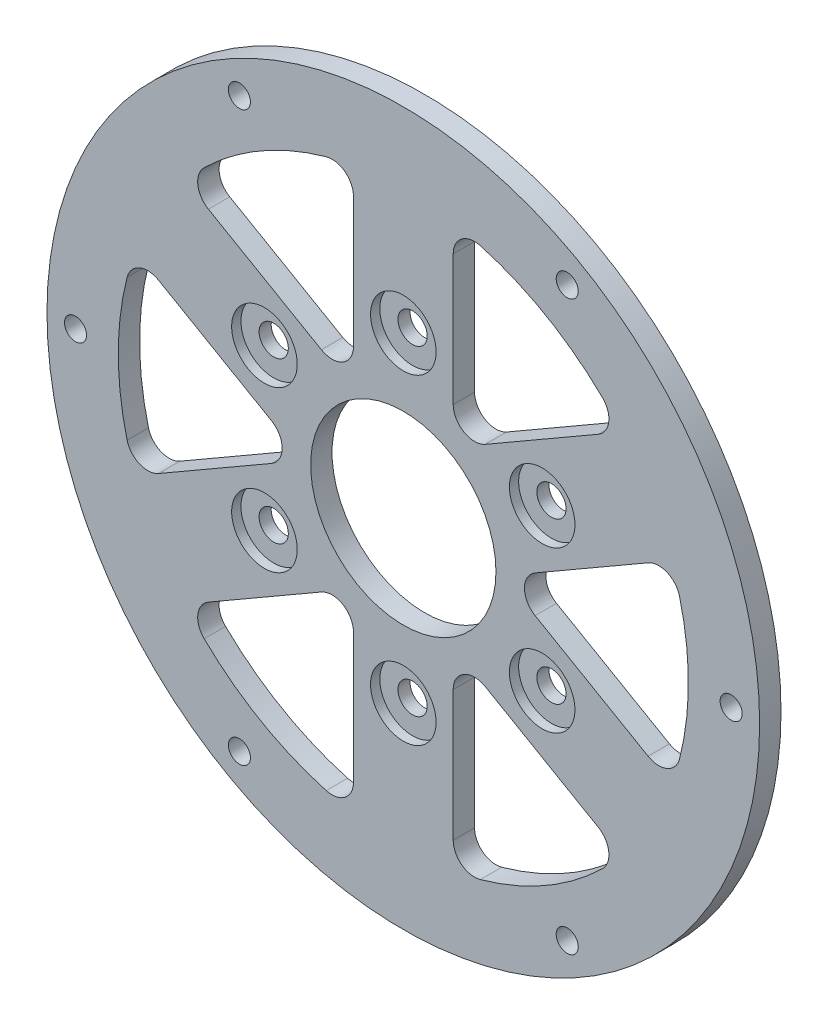
SolidWorks part; units mm, degrees
ref_plane "前视基准面" through (0, 0, 0) normal (0, 0, 1) x (1, 0, 0)
ref_plane "上视基准面" through (0, 0, 0) normal (0, 1, 0) x (1, 0, 0)
ref_plane "右视基准面" through (0, 0, 0) normal (1, 0, 0) x (0, 0, -1)
other "Configuration Table"
sketch "草图1" plane through (0, 0, 0) normal (0, 0, 1) x (1, 0, 0)
  line L0 (42, 0) -> (50, 0) construction
  line L1 (50, 0) -> (52, 0) construction
  line L2 (0, 0) -> (0, 42) construction
  line L3 (0, 0) -> (22.5, 0) construction
  line L4 (14, 0) -> (37.6065, 13.6292)
  line L5 (14, 0) -> (37.6065, -13.6292)
  line L6 (0, 0) -> (19.4856, 11.25) construction
  line L7 (40, 0) -> (42, 0) construction
  line L8 (7, -12.1244) -> (7, -39.3827)
  line L9 (7, -12.1244) -> (30.6065, -25.7535)
  line L10 (-7, -12.1244) -> (-30.6065, -25.7535)
  line L11 (-7, -12.1244) -> (-7, -39.3827)
  line L12 (-14, 0) -> (-37.6065, 13.6292)
  line L13 (-14, 0) -> (-37.6065, -13.6292)
  line L14 (-7, 12.1244) -> (-7, 39.3827)
  line L15 (-7, 12.1244) -> (-30.6065, 25.7535)
  line L16 (7, 12.1244) -> (30.6065, 25.7535)
  line L17 (7, 12.1244) -> (7, 39.3827)
  circle A0 centre (0, 0) radius 50 construction
  circle A1 centre (0, 0) radius 42 construction
  circle A2 centre (46, 0) radius 1.55
  circle A3 centre (23, -39.8372) radius 1.55
  circle A4 centre (-23, -39.8372) radius 1.55
  circle A5 centre (-46, 0) radius 1.55
  circle A6 centre (-23, 39.8372) radius 1.55
  circle A7 centre (23, 39.8372) radius 1.55
  circle A8 centre (0, 0) radius 52
  circle A9 centre (0, 22.5) radius 2.05
  circle A10 centre (0, 0) radius 22.5 construction
  circle A11 centre (19.4856, 11.25) radius 2.05
  circle A12 centre (19.4856, -11.25) radius 2.05
  circle A13 centre (0, -22.5) radius 2.05
  circle A14 centre (-19.4856, -11.25) radius 2.05
  circle A15 centre (-19.4856, 11.25) radius 2.05
  arc A16 (37.6065, 13.6292) -> (37.6065, -13.6292) centre (0, 0) cw
  arc A17 (30.6065, -25.7535) -> (7, -39.3827) centre (0, 0) cw
  arc A18 (-7, -39.3827) -> (-30.6065, -25.7535) centre (0, 0) cw
  arc A19 (-37.6065, -13.6292) -> (-37.6065, 13.6292) centre (0, 0) cw
  arc A20 (-30.6065, 25.7535) -> (-7, 39.3827) centre (0, 0) cw
  arc A21 (7, 39.3827) -> (30.6065, 25.7535) centre (0, 0) cw
  circle A22 centre (0, 0) radius 13
  point P20 (0, 0)
  point P38 (0, 0)
  point P58 (0, 0)
  dimension "D1" = 100
  dimension "D2" = 8
  dimension "D3" = 3.1
  dimension "D4" = 6
  dimension "D6" = 4.1
  dimension "D7" = 45
  dimension "D10" = 6
  dimension "D12" = 26
  dimension "D5" = 2
  dimension "D9" = 7
  dimension "D8" = 6
  dimension "D11" = 6
extrude "凸台-拉伸1" add sketch "草图1" along normal blind 3
fillet "圆角1" radius 3 18 edges at (37.6065, -13.6292, 1.5) (37.6065, 13.6292, 1.5) (14, 0, 1.5) (7, 12.1244, 1.5) (7, 39.3827, 1.5) (30.6065, 25.7535, 1.5) (-30.6065, 25.7535, 1.5) (-7, 39.3827, 1.5) (-7, 12.1244, 1.5) (-37.6065, 13.6292, 1.5) (-37.6065, -13.6292, 1.5) (-14, 0, 1.5) (-30.6065, -25.7535, 1.5) (-7, -39.3827, 1.5) (-7, -12.1244, 1.5) (7, -39.3827, 1.5) (30.6065, -25.7535, 1.5) (7, -12.1244, 1.5)
sketch "草图2" plane through (0, 0, 3) normal (0, 0, 1) x (1, 0, 0)
  line L0 (0, 0) -> (-19.4856, 11.25) construction
  circle A0 centre (-19.4856, 11.25) radius 4.6
  circle A1 centre (0, 22.5) radius 4.6
  circle A2 centre (19.4856, 11.25) radius 4.6
  circle A3 centre (19.4856, -11.25) radius 4.6
  circle A4 centre (0, -22.5) radius 4.6
  circle A5 centre (-19.4856, -11.25) radius 4.6
  point P0 (0, 0)
  point P1 (0, 0)
  point P10 (0, 0)
  point P13 (0, 0)
  point P16 (0, 0)
  point P19 (0, 0)
  dimension "D1" = 9.2
  dimension "D3" = 22.5
  dimension "D2" = 6
extrude "切除-拉伸1" cut sketch "草图2" against normal blind 1.3
sketch "草图3" plane through (0, 0, 3) normal (0, 0, 1) x (1, 0, 0)
  circle A0 centre (0, 0) radius 50
  circle A1 centre (0, 0) radius 68.6551
  dimension "D1" = 100
extrude "切除-拉伸2" cut sketch "草图3" against normal blind 10
